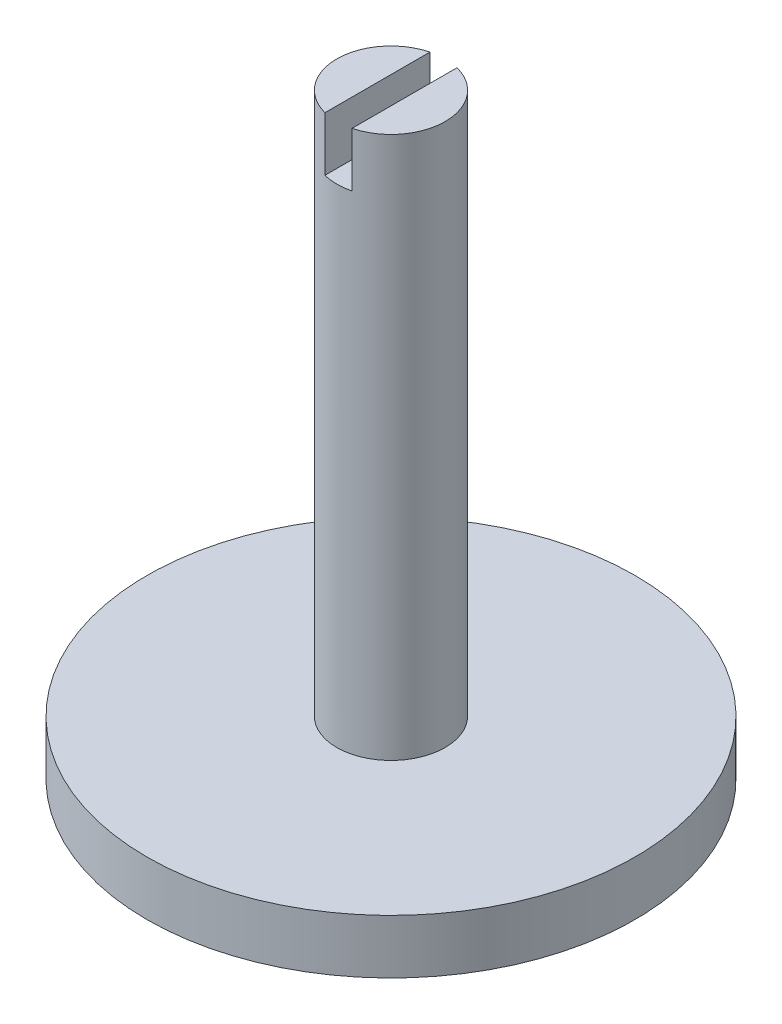
SolidWorks part; units mm, degrees
material "Custom Plastic"
ref_plane "Front Plane" through (0, 0, 0) normal (0, 0, 1) x (1, 0, 0)
ref_plane "Top Plane" through (0, 0, 0) normal (0, 1, 0) x (1, 0, 0)
ref_plane "Right Plane" through (0, 0, 0) normal (1, 0, 0) x (0, 0, -1)
other "Configuration Table"
sketch "Sketch2" plane through (0, 0, 0) normal (0, 1, 0) x (1, 0, 0)
  circle A0 centre (0, 0) radius 57.15
  dimension "D1" = 114.3
extrude "Boss-Extrude1" add sketch "Sketch2" along normal blind 12.7
sketch "Sketch3" plane through (0, 12.7, 0) normal (0, 1, 0) x (1, 0, 0)
  circle A0 centre (0, 0) radius 12.7
  dimension "D1" = 25.4
extrude "Boss-Extrude2" add sketch "Sketch3" along normal blind 127
sketch "Sketch4" plane through (0, 0, 0) normal (0, 0, 1) x (1, 0, 0)
  line L0 (0, 139.7) -> (0, 200.3339) construction
  line L1 (-3.175, 139.7) -> (3.175, 139.7)
  line L2 (-3.175, 139.7) -> (-3.175, 127)
  line L3 (-3.175, 127) -> (3.175, 127)
  line L4 (3.175, 139.7) -> (3.175, 127)
  line L5 (12.7, 139.7) -> (-12.7, 139.7) construction
  line L6 (57.15, 12.7) -> (-57.15, 12.7) construction
  dimension "D1" = 6.35
  dimension "D2" = 127
  dimension "D3" = 12.7
extrude "Cut-Extrude1" cut sketch "Sketch4" against normal through all both and the other way through all
sketch "Sketch5" plane through (0, 139.7, 0) normal (0, 1, 0) x (1, 0, 0)
  circle A0 centre (0, 0) radius 12.7
  dimension "D1" = 25.4
extrude "Cut-Extrude3" [suppressed] cut sketch "Sketch5" against normal up to surface (152.4 mm away)
sketch "Sketch6" plane through (0, 0, 0) normal (0, 0, 1) x (1, 0, 0)
  line L1 (0, 0) -> (-7.9375, 0)
  line L2 (0, 0) -> (0, 25.4)
  line L3 (0, 25.4) -> (-7.9375, 25.4)
  line L4 (-7.9375, 0) -> (-7.9375, 25.4)
  line L5 (0, 0) -> (0, 74.6936) construction
  dimension "D1" = 25.4
  dimension "D2" = 15.875
revolve "Cut-Revolve1" [suppressed] cut sketch "Sketch6" angle 360 about L5
hole_wizard "5/8 (0.341) Diameter Hole1" positions "Sketch7" profile "Sketch8" hole size "5/8" standard "ANSI Inch"
sketch "Sketch7" plane through (0, 0, 0) normal (0, -1, 0) x (-1, 0, 0)
  point P0 (0, 0)
sketch "Sketch8" plane through (0, 0, 0) normal (1, 0, 0) x (0, 0, -1)
  line L0 (0, 0) -> (0, 25.4)
  line L1 (0, 25.4) -> (4.3307, 22.7979)
  line L2 (4.3307, 22.7979) -> (4.3307, 0)
  line L5 (4.3307, 0) -> (0, 0)
  line L10 (0, 25.4) -> (-4.3307, 22.7979) construction
  line L11 (0, -6.35) -> (0, 107.95) construction
  dimension "Hole Dia." = 8.6614
  dimension "Hole Depth" = 25.4
  dimension "Drill Angle" = 118
